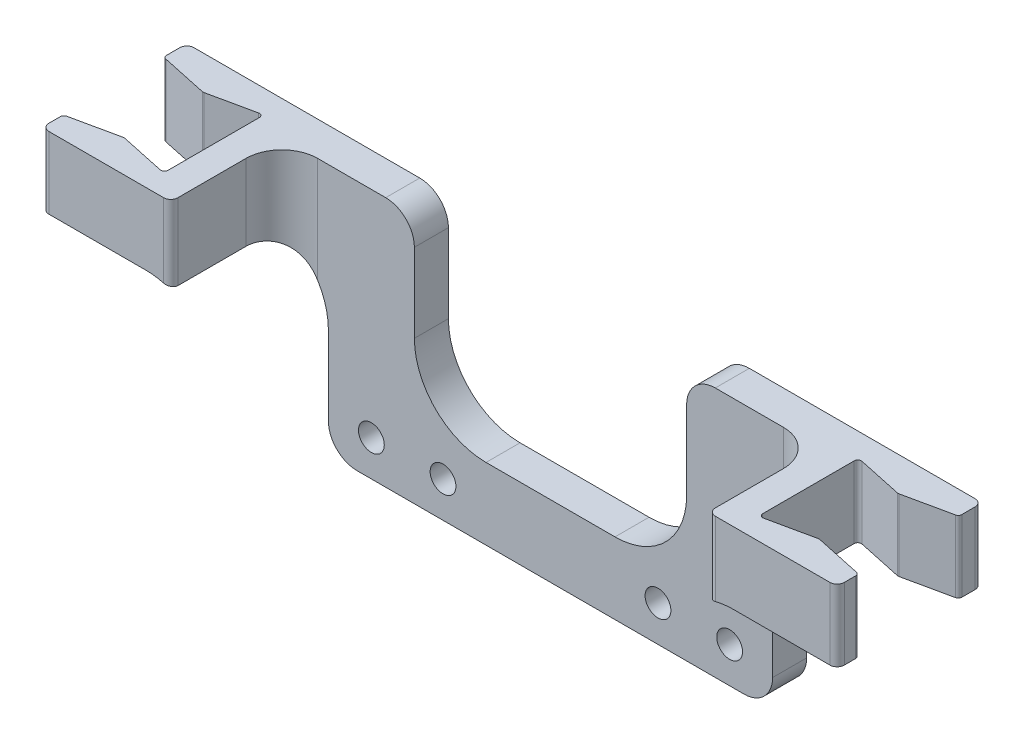
SolidWorks part; units mm, degrees
ref_plane "正面" through (0, 0, 0) normal (0, 0, 1) x (1, 0, 0)
ref_plane "平面" through (0, 0, 0) normal (0, 1, 0) x (1, 0, 0)
ref_plane "右側面" through (0, 0, 0) normal (1, 0, 0) x (0, 0, -1)
sketch "ｽｹｯﾁ1" plane through (0, 0, 0) normal (0, 0, 1) x (1, 0, 0)
  line L0 (56.5, 563.3554) -> (56.5, -236.6446) construction
  line L1 (55.5, -116) -> (-55.5, -116)
  line L2 (55.5, -116) -> (55.5, -81)
  line L3 (55.5, -81) -> (-55.5, -81)
  line L4 (-55.5, -116) -> (-55.5, -81)
  line L5 (-56.5, 563.3554) -> (-56.5, -236.6446) construction
  line L6 (0, -116) -> (0, -81) construction
  circle A0 centre (15, -111) radius 1.6 construction
  circle A1 centre (15, -111) radius 1.6 construction
  circle A2 centre (25, -111) radius 1.8
  circle A3 centre (15, -111) radius 1.8
  circle A4 centre (-15, -111) radius 1.8
  circle A5 centre (-25, -111) radius 1.8
  dimension "D3" = 5
  dimension "D4" = 30
  dimension "D5" = 3.6
  dimension "D1" = 1
  dimension "D2" = 1
extrude "ﾎﾞｽ - 押し出し1" add sketch "ｽｹｯﾁ1" along normal blind 4.75
sketch "ｽｹｯﾁ2" plane through (0, 0, 4.75) normal (0, 0, 1) x (1, 0, 0)
  line L0 (-55.5, -116) -> (55.5, -116) construction
  line L1 (41.5, -116) -> (37.5, -116)
  line L2 (41.5, -116) -> (41.5, -81)
  line L3 (41.5, -81) -> (37.5, -81)
  line L4 (37.5, -116) -> (37.5, -81)
  line L5 (55.5, -81) -> (-55.5, -81) construction
  line L6 (0, -116) -> (0, -81) construction
  line L11 (-41.5, -81) -> (-37.5, -81)
  line L12 (-37.5, -116) -> (-37.5, -81)
  line L13 (-41.5, -116) -> (-37.5, -116)
  line L14 (-41.5, -116) -> (-41.5, -81)
  line L15 (55.5, -116) -> (55.5, -81) construction
  dimension "D1" = 14
  dimension "D2" = 4
extrude "ﾎﾞｽ - 押し出し2" add sketch "ｽｹｯﾁ2" along normal blind 15.5
sketch "ｽｹｯﾁ3" plane through (41.5, 0, 0) normal (1, 0, 0) x (0, 0, -1)
  line L0 (-20.25, -81) -> (-4.75, -81) construction
  line L1 (-20.25, -116) -> (-15.75, -116)
  line L2 (-20.25, -116) -> (-20.25, -81)
  line L3 (-20.25, -81) -> (-15.75, -81)
  line L4 (-15.75, -116) -> (-15.75, -81)
  dimension "D1" = 4.5
extrude "ﾎﾞｽ - 押し出し3" add sketch "ｽｹｯﾁ3" along normal blind 14
sketch "ｽｹｯﾁ4" plane through (-41.5, 0, 0) normal (-1, 0, 0) x (0, 0, 1)
  line L0 (20.25, -81) -> (4.75, -81) construction
  line L1 (20.25, -116) -> (15.75, -116)
  line L2 (20.25, -116) -> (20.25, -81)
  line L3 (20.25, -81) -> (15.75, -81)
  line L4 (15.75, -116) -> (15.75, -81)
  dimension "D1" = 4.5
extrude "ﾎﾞｽ - 押し出し4" add sketch "ｽｹｯﾁ4" along normal blind 14
fillet "ﾌｨﾚｯﾄ1" radius 5 2 edges at (37.5, -98.5, 4.75) (-37.5, -98.5, 4.75)
fillet "ﾌｨﾚｯﾄ2" radius 1 6 edges at (55.5, -98.5, 0) (-55.5, -98.5, 0) (-55.5, -98.5, 20.25) (55.5, -98.5, 20.25) (37.5, -98.5, 20.25) (-37.5, -98.5, 20.25)
sketch "ｽｹｯﾁ5" plane through (0, -81, 0) normal (0, 1, 0) x (1, 0, 0)
  line L0 (32.5, -4.75) -> (-32.5, -4.75) construction
  line L1 (-10, -4.75) -> (10, -4.75)
  line L2 (-10, -4.75) -> (-10, -2.75)
  line L3 (-10, -2.75) -> (10, -2.75)
  line L4 (10, -4.75) -> (10, -2.75)
  line L5 (54.5, 0) -> (-54.5, 0) construction
  point P6 (0, -2.75)
  point P9 (0, 0)
  dimension "D1" = 0
  dimension "D2" = 20
  dimension "D3" = 2
extrude "ｶｯﾄ - 押し出し1" cut sketch "ｽｹｯﾁ5" against normal blind 1
fillet "ﾌｨﾚｯﾄ4" [suppressed] radius 3
fillet "ﾌｨﾚｯﾄ5" [suppressed] radius 2
sketch "ｽｹｯﾁ6" plane through (0, -81, 0) normal (0, 1, 0) x (1, 0, 0)
  line L0 (-48.5, -15.75) -> (-55.5, -17.25)
  line L1 (-55.5, -15.75) -> (-41.5, -15.75) construction
  line L2 (-55.5, -19.25) -> (-55.5, -15.75) construction
  line L3 (-55.5, -17.25) -> (-55.5, -15.75)
  line L4 (-55.5, -15.75) -> (-41.5, -15.75)
  line L5 (-48.5, -4.75) -> (-48.5, -15.75) construction
  line L6 (-41.5, -4.75) -> (-55.5, -4.75) construction
  line L7 (-41.5, -10.25) -> (-48.5, -10.25) construction
  line L8 (-41.5, -15.75) -> (-41.5, -4.75) construction
  line L9 (0, -2.75) -> (0, -23.4017) construction
  line L10 (10, -2.75) -> (-10, -2.75) construction
  line L11 (-41.5, -17.25) -> (-41.5, -15.75)
  line L12 (-48.5, -15.75) -> (-41.5, -17.25)
  line L13 (-41.5, -3.25) -> (-41.5, -4.75)
  line L14 (-48.5, -4.75) -> (-41.5, -3.25)
  line L15 (-55.5, -3.25) -> (-55.5, -4.75)
  line L16 (-48.5, -4.75) -> (-55.5, -3.25)
  line L17 (-55.5, -4.75) -> (-41.5, -4.75)
  line L18 (55.5, -3.25) -> (55.5, -4.75)
  line L19 (48.5, -4.75) -> (55.5, -3.25)
  line L20 (41.5, -3.25) -> (41.5, -4.75)
  line L21 (55.5, -4.75) -> (41.5, -4.75)
  line L22 (48.5, -4.75) -> (41.5, -3.25)
  line L23 (41.5, -17.25) -> (41.5, -15.75)
  line L24 (48.5, -15.75) -> (41.5, -17.25)
  line L25 (55.5, -17.25) -> (55.5, -15.75)
  line L26 (48.5, -15.75) -> (55.5, -17.25)
  line L27 (55.5, -15.75) -> (41.5, -15.75)
  line M22 (55.5, -19.25) -> (55.5, -15.75)
  line M23 (55.5, -15.75) -> (41.5, -15.75)
  line M25 (41.5, -4.75) -> (55.5, -4.75)
  line M26 (55.5, -4.75) -> (55.5, -1)
  line M30 (-55.5, -1) -> (-55.5, -4.75)
  line M31 (-55.5, -4.75) -> (-41.5, -4.75)
  line M33 (-41.5, -15.75) -> (-55.5, -15.75)
  line M34 (-55.5, -15.75) -> (-55.5, -19.25)
  dimension "D1" = 1.5
extrude "ｶｯﾄ - 押し出し2" cut sketch "ｽｹｯﾁ6" against normal blind 200 contours L16 M31 M30 | L14 L13 M31 | L12 L11 M33 | L0 M33 M34 | L19 M25 M26 | L22 L20 M25 | L26 M23 M22 | L24 L23 M23
fillet "ﾌｨﾚｯﾄ6" [suppressed] radius 0.5
fillet "ﾌｨﾚｯﾄ7" [suppressed] radius 1
sketch "ｽｹｯﾁ8" plane through (0, 0, 0) normal (0, 0, -1) x (-1, 0, 0)
  line L0 (54.5, -116) -> (-54.5, -116) construction
  line L1 (-31, -116) -> (-64.5, -116)
  line L2 (-31, -116) -> (-31, -91)
  line L3 (-31, -91) -> (-64.5, -91)
  line L4 (-64.5, -116) -> (-64.5, -91)
  line L5 (-54.5, -81) -> (54.5, -81) construction
  line L6 (-19, -81) -> (19, -81)
  line L7 (-19, -81) -> (-19, -106)
  line L8 (-19, -106) -> (19, -106)
  line L9 (0, -81) -> (0, -106)
  line L10 (-54.5, -81) -> (-54.5, -116) construction
  line L11 (19, -81) -> (19, -106)
  line L12 (31, -91) -> (64.5, -91)
  line L13 (64.5, -116) -> (64.5, -91)
  line L14 (31, -116) -> (64.5, -116)
  line L15 (31, -116) -> (31, -91)
  circle A0 centre (-15, -111) radius 1.8 construction
  circle A1 centre (-25, -111) radius 1.8 construction
  point P12 (0, -81)
  line M9 (54.5, -81) -> (-54.5, -81)
  line M10 (-54.5, -81) -> (-54.5, -116)
  line M11 (-54.5, -116) -> (54.5, -116)
  line M12 (54.5, -116) -> (54.5, -81)
  dimension "D1" = 5
  dimension "D3" = 6
  dimension "D5" = 6
  dimension "D2" = 10
  dimension "D4" = 10
extrude "ｶｯﾄ - 押し出し3" cut sketch "ｽｹｯﾁ8" against normal blind 1000 contours L9 L6 L7 L8 | L11 L9 L8 M9 | L2 L3 M10 M11 | L15 L12 M11 M12
fillet "ﾌｨﾚｯﾄ8" radius 10 4 edges at (-31, -91, 2.375) (31, -91, 2.375) (-19, -106, 2.375) (19, -106, 2.375)
fillet "ﾌｨﾚｯﾄ9" radius 4 4 edges at (31, -116, 2.375) (-31, -116, 2.375) (19, -81, 2.375) (-19, -81, 2.375)
fillet "ﾌｨﾚｯﾄ10" radius 0.5 12 edges at (-55.5, -86, 17.25) (-48.5, -86, 15.75) (-41.5, -86, 17.25) (-41.5, -86, 3.25) (-48.5, -86, 4.75) (-55.5, -86, 3.25) (55.5, -86, 17.25) (41.5, -86, 17.25) (48.5, -86, 15.75) (41.5, -86, 3.25) (48.5, -86, 4.75) (55.5, -86, 3.25)
